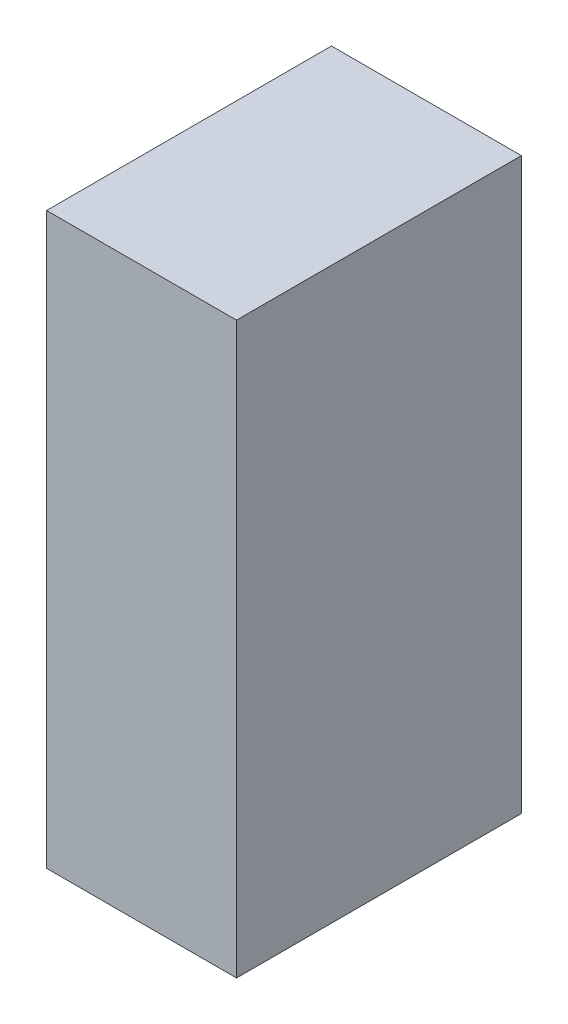
SolidWorks part; units mm, degrees
ref_plane "Front Plane" through (0, 0, 0) normal (0, 0, 1) x (1, 0, 0)
ref_plane "Top Plane" through (0, 0, 0) normal (0, 1, 0) x (1, 0, 0)
ref_plane "Right Plane" through (0, 0, 0) normal (1, 0, 0) x (0, 0, -1)
sketch "Sketch1" plane through (0, 0, 0) normal (0, 1, 0) x (1, 0, 0)
  line L1 (-2, -3) -> (2, -3)
  line L2 (-2, -3) -> (-2, 3)
  line L3 (-2, 3) -> (2, 3)
  line L4 (2, -3) -> (2, 3)
  line L5 (-2, -3) -> (2, 3) construction
  line L6 (-2, 3) -> (2, -3) construction
  point P0 (0, 0)
  dimension "D1" = 6
  dimension "D2" = 4
extrude "Boss-Extrude1" add sketch "Sketch1" along normal blind 12
